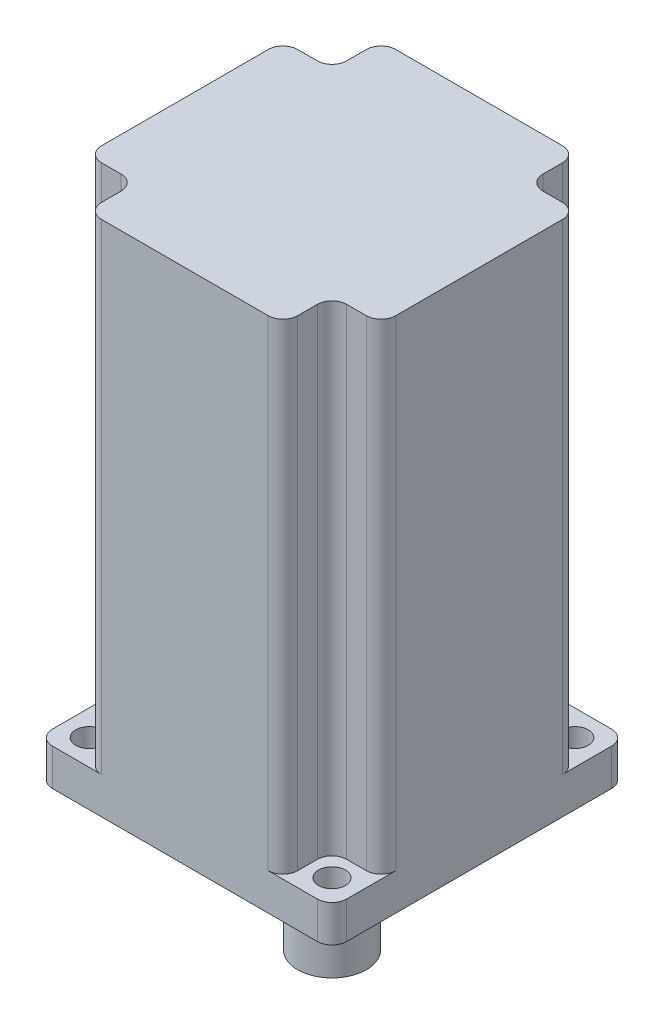
SolidWorks part; units mm, degrees
ref_plane "Front Plane" through (0, 0, 0) normal (0, 0, 1) x (1, 0, 0)
ref_plane "Top Plane" through (0, 0, 0) normal (0, 1, 0) x (1, 0, 0)
ref_plane "Right Plane" through (0, 0, 0) normal (1, 0, 0) x (0, 0, -1)
sketch "Sketch1" plane through (0, 0, 0) normal (0, 1, 0) x (1, 0, 0)
  line L0 (-55, 0) -> (55, 0) construction
  line L1 (-27, -30) -> (27, -30)
  line L2 (-30, -27) -> (-30, 27)
  line L3 (-27, 30) -> (27, 30)
  line L4 (30, -27) -> (30, 27)
  line L5 (-30, -30) -> (30, 30) construction
  line L6 (-30, 30) -> (30, -30) construction
  arc A0 (-27, -30) -> (-30, -27) centre (-27, -27) cw
  arc A1 (27, -30) -> (30, -27) centre (27, -27) ccw
  arc A2 (27, 30) -> (30, 27) centre (27, 27) cw
  arc A3 (-30, 27) -> (-27, 30) centre (-27, 27) cw
  circle A4 centre (0, 0) radius 35 construction
  circle A5 centre (-24.7487, 24.7487) radius 2.75
  circle A6 centre (24.7487, 24.7487) radius 2.75
  circle A7 centre (-24.7487, -24.7487) radius 2.75
  circle A8 centre (24.7487, -24.7487) radius 2.75
  point P0 (0, 0)
  dimension "D3" = 3
  dimension "D4" = 70
  dimension "D5" = 5.5
  dimension "D1" = 60
  dimension "D2" = 60
extrude "Boss-Extrude1" add sketch "Sketch1" along normal blind 7.5
sketch "Sketch2" plane through (0, 7.5, 0) normal (0, 1, 0) x (1, 0, 0)
  line L0 (27, 30) -> (-27, 30) construction
  line L1 (-20, 30) -> (20, 30)
  line L2 (20, 30) -> (20, 20)
  line L3 (20, 20) -> (30, 20)
  line L4 (30, -27) -> (30, 27) construction
  line L5 (30, 20) -> (30, -20)
  line L6 (30, -20) -> (20, -20)
  line L7 (20, -20) -> (20, -30)
  line L8 (-27, -30) -> (27, -30) construction
  line L9 (20, -30) -> (-20, -30)
  line L10 (-20, -30) -> (-20, -20)
  line L11 (-20, -20) -> (-30, -20)
  line L12 (-30, 27) -> (-30, -27) construction
  line L13 (-30, -20) -> (-30, 20)
  line L14 (-30, 20) -> (-20, 20)
  line L15 (-20, 20) -> (-20, 30)
  dimension "D1" = 10
extrude "Boss-Extrude2" add sketch "Sketch2" along normal blind 98
fillet "Fillet1" radius 3 12 edges at (20, 56.5, -20) (20, 56.5, -30) (30, 56.5, -20) (-20, 56.5, -30) (-20, 56.5, -20) (-30, 56.5, -20) (-30, 56.5, 20) (-20, 56.5, 20) (-20, 56.5, 30) (20, 56.5, 30) (20, 56.5, 20) (30, 56.5, 20)
sketch "Sketch4" plane through (0, 0, 0) normal (0, -1, 0) x (1, 0, 0)
  circle A0 centre (0, 0) radius 25
  dimension "D1" = 50
extrude "Boss-Extrude4" add sketch "Sketch4" along normal blind 3
sketch "Sketch5" plane through (0, -3, 0) normal (0, -1, 0) x (1, 0, 0)
  circle A0 centre (0, 0) radius 7
  dimension "D1" = 14
extrude "Boss-Extrude5" add sketch "Sketch5" along normal blind 27
